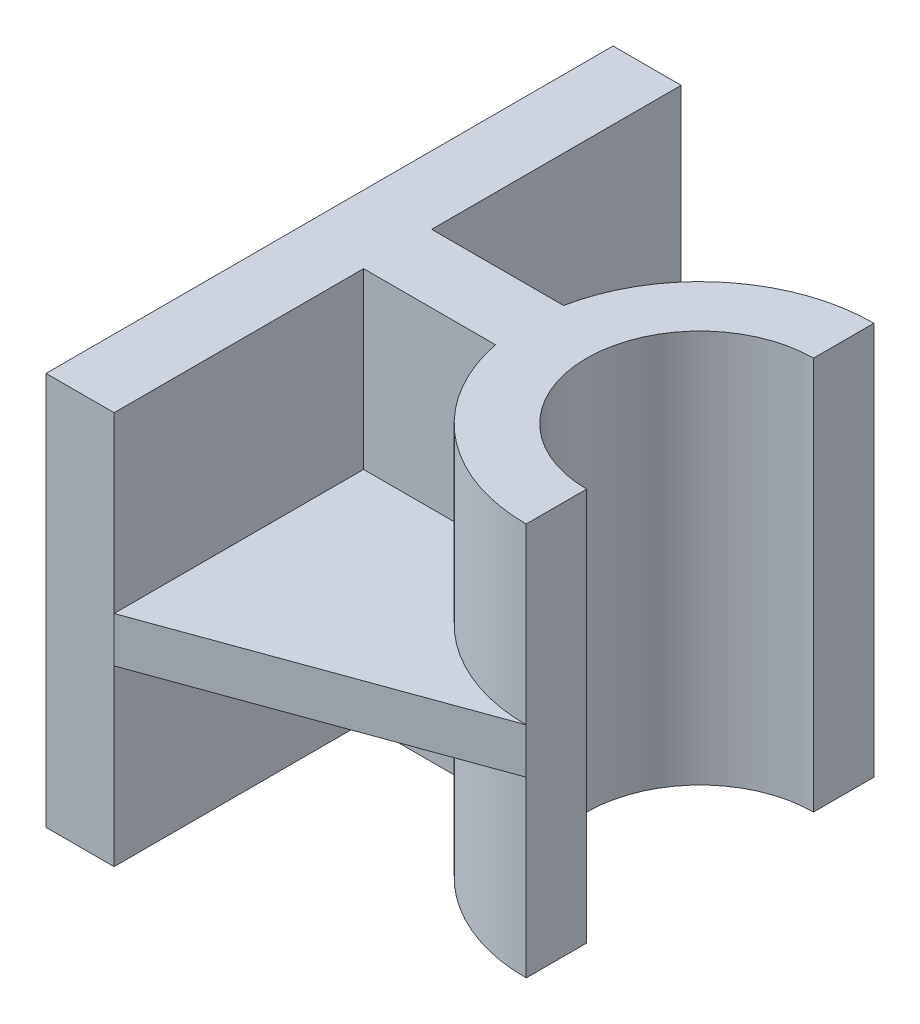
SolidWorks part; units mm, degrees
ref_plane "Front Plane" through (0, 0, 0) normal (0, 0, 1) x (1, 0, 0)
ref_plane "Top Plane" through (0, 0, 0) normal (0, 1, 0) x (1, 0, 0)
ref_plane "Right Plane" through (0, 0, 0) normal (1, 0, 0) x (0, 0, -1)
sketch "Sketch1" plane through (0, 0, 0) normal (0, 1, 0) x (1, 0, 0)
  line L0 (4.5, 0) -> (44.5, 0) construction
  line L1 (4.5, -37.5) -> (-4.5, -37.5)
  line L2 (4.5, -37.5) -> (4.5, 37.5)
  line L3 (4.5, 37.5) -> (-4.5, 37.5)
  line L4 (-4.5, -37.5) -> (-4.5, 37.5)
  line L5 (4.5, -37.5) -> (-4.5, 37.5) construction
  line L6 (4.5, 37.5) -> (-4.5, -37.5) construction
  line L7 (44.5, 23) -> (44.5, 15)
  line L8 (44.5, -15) -> (44.5, -23)
  line L10 (4.5, -4.5) -> (21.9445, -4.5)
  line L11 (4.5, -4.5) -> (4.5, 4.5)
  line L12 (4.5, 4.5) -> (21.9445, 4.5)
  arc A0 (44.5, -23) -> (44.5, 23) centre (44.5, 0) cw
  arc A1 (44.5, -15) -> (44.5, 15) centre (44.5, 0) cw
  point P0 (0, 0)
  dimension "D4" = 15
  dimension "D5" = 23
  dimension "D1" = 75
  dimension "D2" = 9
  dimension "D3" = 40
  dimension "D6" = 8
  dimension "D7" = 8
  dimension "D8" = 9
extrude "Boss-Extrude1" add sketch "Sketch1" against normal mid plane 52 contours L4 L1 L2 L3 | L10 A0 L12 L2 | L8 A1 L7 A0
sketch "Sketch3" plane through (0, 0, 0) normal (0, 1, 0) x (1, 0, 0)
  line L0 (44.5, -23) -> (4.5, -37.5)
rib "Rib3" sketch "Sketch3" sketch "Sketch3" thickness 6 extrusion direction parallel to sketch draft on no parameters "D1"=6
